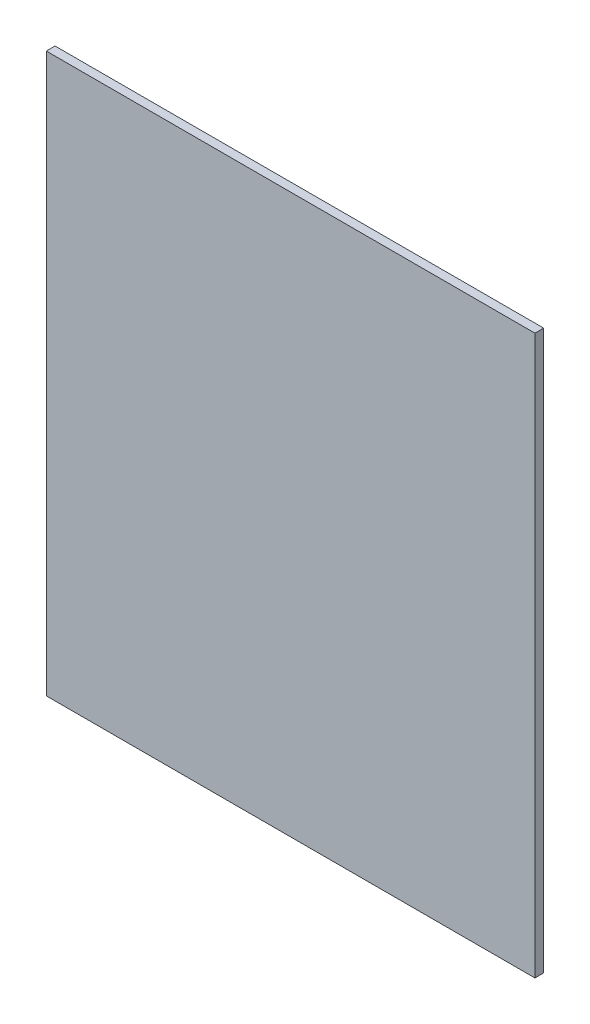
SolidWorks part; units mm, degrees
ref_plane "Front Plane" through (0, 0, 0) normal (0, 0, 1) x (1, 0, 0)
ref_plane "Top Plane" through (0, 0, 0) normal (0, 1, 0) x (1, 0, 0)
ref_plane "Right Plane" through (0, 0, 0) normal (1, 0, 0) x (0, 0, -1)
sketch "Sketch1" plane through (0, 0, 0) normal (0, 0, 1) x (1, 0, 0)
  line L0 (533.4, 609.6) -> (-533.4, -609.6) construction
  line L1 (-533.4, 609.6) -> (533.4, 609.6)
  line L2 (-533.4, 609.6) -> (-533.4, -609.6)
  line L3 (-533.4, -609.6) -> (533.4, -609.6)
  line L4 (533.4, 609.6) -> (533.4, -609.6)
  point P6 (0, 0)
  dimension "D1" = 1219.2
  dimension "D2" = 1066.8
extrude "Boss-Extrude1" add sketch "Sketch1" along normal blind 19.05
